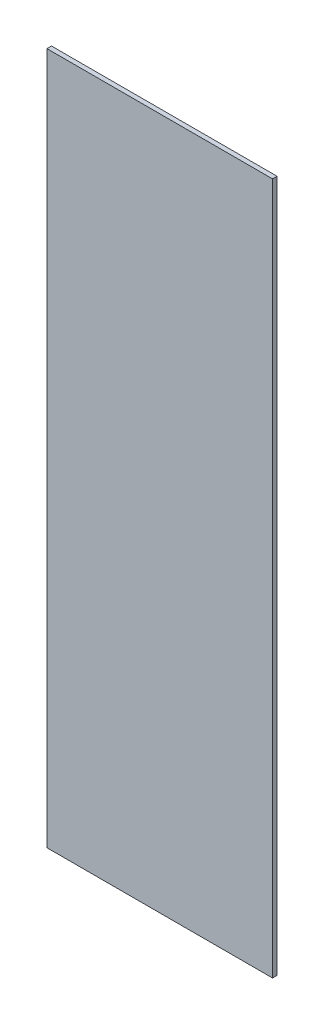
SolidWorks part; units mm, degrees
material "ABS"
ref_plane "X-Y Datum" through (0, 0, 0) normal (0, 0, 1) x (1, 0, 0)
ref_plane "X-Z Datum" through (0, 0, 0) normal (0, 1, 0) x (1, 0, 0)
ref_plane "Y-Z Datum" through (0, 0, 0) normal (1, 0, 0) x (0, 0, -1)
sketch "Sketch1" plane through (0, 0, 0) normal (0, 0, 1) x (1, 0, 0)
  line L0 (-2.6736, 120.0341) -> (76.2139, 120.0341)
  line L1 (-2.6736, 120.0341) -> (-2.6736, -122.0259)
  line L2 (-2.6736, -122.0259) -> (76.2139, -122.0259)
  line L3 (76.2139, 120.0341) -> (76.2139, -122.0259)
extrude "Boss-Extrude1" add sketch "Sketch1" along normal blind 1.5875
